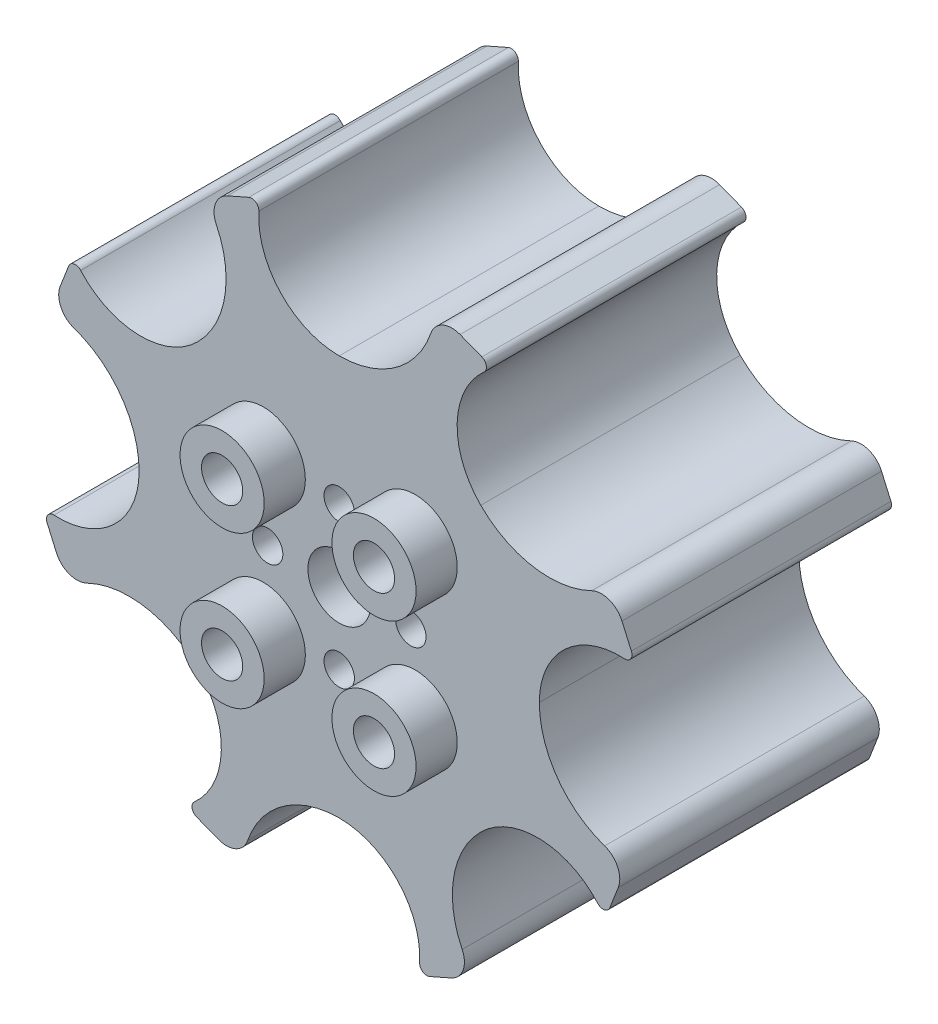
SolidWorks part; units mm, degrees
material "6061-T6 (SS)"
ref_plane "前视基准面" through (0, 0, 0) normal (0, 0, 1) x (1, 0, 0)
ref_plane "上视基准面" through (0, 0, 0) normal (0, 1, 0) x (1, 0, 0)
ref_plane "右视基准面" through (0, 0, 0) normal (1, 0, 0) x (0, 0, -1)
sketch "草图1" plane through (0, 0, 0) normal (0, 0, 1) x (1, 0, 0)
  line L0 (0, 31.3575) -> (0, 0) construction
  line L1 (0, 0) -> (22.1731, 22.1731) construction
  line L4 (0, 31.3575) -> (22.1731, 22.1731) construction
  line L6 (11.6409, 26.5357) -> (12.5976, 28.8454) construction
  line L7 (22.2808, 22.9688) -> (16.1797, 28.8872) construction
  line L8 (22.2808, 22.9688) -> (28.5472, 29.4288) construction
  line L9 (15.9368, 30.2296) -> (13.5034, 31.1755)
  line L17 (0, 33.18) -> (0, 31.3575) construction
  line L18 (32.6446, 10.1066) -> (31.5928, 12.4961)
  line L19 (30.2296, -15.9368) -> (31.1755, -13.5034)
  line L20 (10.1066, -32.6446) -> (12.4961, -31.5928)
  line L21 (-15.9368, -30.2296) -> (-13.5034, -31.1755)
  line L22 (-32.6446, -10.1066) -> (-31.5928, -12.4961)
  line L23 (-30.2296, 15.9368) -> (-31.1755, 13.5034)
  line L24 (-10.1066, 32.6446) -> (-12.4961, 31.5928)
  circle A0 centre (0, 0) radius 31.3575 construction
  arc A9 (16.1797, 28.8872) -> (15.8091, 15.8091) centre (22.1731, 22.1731) ccw
  circle A13 centre (0, 0) radius 41 construction
  arc A16 (16.1797, 28.8872) -> (15.9368, 30.2296) centre (15.6469, 29.484) ccw
  arc A17 (13.5034, 31.1755) -> (10.2336, 29.6588) centre (12.5976, 28.8454) ccw
  arc A18 (0, 22.3575) -> (10.2336, 29.6588) centre (0, 33.18) ccw
  arc A19 (15.8091, 15.8091) -> (28.2082, 13.7357) centre (23.4618, 23.4618) ccw
  arc A20 (31.5928, 12.4961) -> (28.2082, 13.7357) centre (29.3046, 11.4889) ccw
  arc A21 (31.8671, 8.9856) -> (32.6446, 10.1066) centre (31.9124, 9.7843) ccw
  arc A22 (31.8671, 8.9856) -> (22.3575, 0) centre (31.3575, 0) ccw
  arc A23 (22.3575, 0) -> (29.6588, -10.2336) centre (33.18, 0) ccw
  arc A24 (31.1755, -13.5034) -> (29.6588, -10.2336) centre (28.8454, -12.5976) ccw
  arc A25 (28.8872, -16.1797) -> (30.2296, -15.9368) centre (29.484, -15.6469) ccw
  arc A26 (28.8872, -16.1797) -> (15.8091, -15.8091) centre (22.1731, -22.1731) ccw
  arc A27 (15.8091, -15.8091) -> (13.7357, -28.2082) centre (23.4618, -23.4618) ccw
  arc A28 (12.4961, -31.5928) -> (13.7357, -28.2082) centre (11.4889, -29.3046) ccw
  arc A29 (8.9856, -31.8671) -> (10.1066, -32.6446) centre (9.7843, -31.9124) ccw
  arc A30 (8.9856, -31.8671) -> (0, -22.3575) centre (0, -31.3575) ccw
  arc A31 (0, -22.3575) -> (-10.2336, -29.6588) centre (0, -33.18) ccw
  arc A32 (-13.5034, -31.1755) -> (-10.2336, -29.6588) centre (-12.5976, -28.8454) ccw
  arc A33 (-16.1797, -28.8872) -> (-15.9368, -30.2296) centre (-15.6469, -29.484) ccw
  arc A34 (-16.1797, -28.8872) -> (-15.8091, -15.8091) centre (-22.1731, -22.1731) ccw
  arc A35 (-15.8091, -15.8091) -> (-28.2082, -13.7357) centre (-23.4618, -23.4618) ccw
  arc A36 (-31.5928, -12.4961) -> (-28.2082, -13.7357) centre (-29.3046, -11.4889) ccw
  arc A37 (-31.8671, -8.9856) -> (-32.6446, -10.1066) centre (-31.9124, -9.7843) ccw
  arc A38 (-31.8671, -8.9856) -> (-22.3575, 0) centre (-31.3575, 0) ccw
  arc A39 (-22.3575, 0) -> (-29.6588, 10.2336) centre (-33.18, 0) ccw
  arc A40 (-31.1755, 13.5034) -> (-29.6588, 10.2336) centre (-28.8454, 12.5976) ccw
  arc A41 (-28.8872, 16.1797) -> (-30.2296, 15.9368) centre (-29.484, 15.6469) ccw
  arc A42 (-28.8872, 16.1797) -> (-15.8091, 15.8091) centre (-22.1731, 22.1731) ccw
  arc A43 (-15.8091, 15.8091) -> (-13.7357, 28.2082) centre (-23.4618, 23.4618) ccw
  arc A44 (-12.4961, 31.5928) -> (-13.7357, 28.2082) centre (-11.4889, 29.3046) ccw
  arc A45 (-8.9856, 31.8671) -> (-10.1066, 32.6446) centre (-9.7843, 31.9124) ccw
  arc A46 (-8.9856, 31.8671) -> (0, 22.3575) centre (0, 31.3575) ccw
  point P91 (0, 0)
  point P98 (0, 0)
  dimension "D1" = 9
  dimension "D3" = 45
  dimension "D4" = 8
  dimension "D5" = 9
  dimension "D8" = 82
  dimension "D9" = 9
  dimension "D10" = 2.5
  dimension "D11" = 0.8
  dimension "D2" = 24
  dimension "D6" = 11.4
  dimension "D7" = 2.5
  dimension "D13" = 8.5
extrude "凸台-拉伸1" add sketch "草图1" along normal blind 25
sketch "草图2" plane through (0, 0, 0) normal (0, 0, -1) x (-1, 0, 0)
  line L0 (0, 0) -> (22.3575, 0) construction
  line L1 (0, 0) -> (15.8091, -15.8091) construction
  arc A0 (19.3575, 0) -> (21.9475, -7.4466) centre (31.3575, 0) ccw
  arc A1 (21.0346, -9.8541) -> (13.6878, -13.6878) centre (23.4618, -23.4618) ccw
  arc A2 (21.0346, -9.8541) -> (21.9475, -7.4466) centre (20.7712, -8.3774) ccw
  arc A3 (22.3575, 0) -> (31.8671, -8.9856) centre (31.3575, 0) ccw construction
  arc A4 (13.6878, -13.6878) -> (10.2537, -20.7847) centre (22.1731, -22.1731) ccw
  arc A5 (7.9058, -21.8416) -> (10.2537, -20.7847) centre (8.7638, -20.6112) ccw
  arc A27 (28.2082, -13.7357) -> (15.8091, -15.8091) centre (23.4618, -23.4618) ccw construction
  arc A28 (7.9058, -21.8416) -> (0, -19.3575) centre (0, -33.18) ccw
  arc A29 (0, -19.3575) -> (-7.4466, -21.9475) centre (0, -31.3575) ccw
  arc A30 (-9.8541, -21.0346) -> (-7.4466, -21.9475) centre (-8.3774, -20.7712) ccw
  arc A31 (-9.8541, -21.0346) -> (-13.6878, -13.6878) centre (-23.4618, -23.4618) ccw
  arc A32 (-13.6878, -13.6878) -> (-20.7847, -10.2537) centre (-22.1731, -22.1731) ccw
  arc A33 (-21.8416, -7.9058) -> (-20.7847, -10.2537) centre (-20.6112, -8.7638) ccw
  arc A34 (-21.8416, -7.9058) -> (-19.3575, 0) centre (-33.18, 0) ccw
  arc A35 (-19.3575, 0) -> (-21.9475, 7.4466) centre (-31.3575, 0) ccw
  arc A36 (-21.0346, 9.8541) -> (-21.9475, 7.4466) centre (-20.7712, 8.3774) ccw
  arc A37 (-21.0346, 9.8541) -> (-13.6878, 13.6878) centre (-23.4618, 23.4618) ccw
  arc A38 (-13.6878, 13.6878) -> (-10.2537, 20.7847) centre (-22.1731, 22.1731) ccw
  arc A39 (-7.9058, 21.8416) -> (-10.2537, 20.7847) centre (-8.7638, 20.6112) ccw
  arc A40 (-7.9058, 21.8416) -> (0, 19.3575) centre (0, 33.18) ccw
  arc A41 (0, 19.3575) -> (7.4466, 21.9475) centre (0, 31.3575) ccw
  arc A42 (9.8541, 21.0346) -> (7.4466, 21.9475) centre (8.3774, 20.7712) ccw
  arc A43 (9.8541, 21.0346) -> (13.6878, 13.6878) centre (23.4618, 23.4618) ccw
  arc A44 (13.6878, 13.6878) -> (20.7847, 10.2537) centre (22.1731, 22.1731) ccw
  arc A45 (21.8416, 7.9058) -> (20.7847, 10.2537) centre (20.6112, 8.7638) ccw
  arc A46 (21.8416, 7.9058) -> (19.3575, 0) centre (33.18, 0) ccw
  point P69 (0, 0)
  dimension "D1" = 3
  dimension "D2" = 3
  dimension "D3" = 1.5
  dimension "D4" = 8
extrude "切除-拉伸1" cut sketch "草图2" against normal through all
sketch "草图3" plane through (0, 0, 25) normal (0, 0, 1) x (1, 0, 0)
  line L8 (15.9368, 30.2296) -> (13.5034, 31.1755)
  line L9 (-10.1066, 32.6446) -> (-12.4961, 31.5928)
  line L10 (-30.2296, 15.9368) -> (-31.1755, 13.5034)
  line L11 (-32.6446, -10.1066) -> (-31.5928, -12.4961)
  line L12 (-15.9368, -30.2296) -> (-13.5034, -31.1755)
  line L13 (10.1066, -32.6446) -> (12.4961, -31.5928)
  line L14 (30.2296, -15.9368) -> (31.1755, -13.5034)
  line L15 (32.6446, 10.1066) -> (31.5928, 12.4961)
  line L16 (15.9368, 30.2296) -> (13.5034, 31.1755)
  line L17 (-10.1066, 32.6446) -> (-12.4961, 31.5928)
  line L18 (-30.2296, 15.9368) -> (-31.1755, 13.5034)
  line L19 (-32.6446, -10.1066) -> (-31.5928, -12.4961)
  line L20 (-15.9368, -30.2296) -> (-13.5034, -31.1755)
  line L21 (10.1066, -32.6446) -> (12.4961, -31.5928)
  line L22 (30.2296, -15.9368) -> (31.1755, -13.5034)
  line L23 (32.6446, 10.1066) -> (31.5928, 12.4961)
  arc A32 (15.8091, 15.8091) -> (28.2082, 13.7357) centre (23.4618, 23.4618) ccw
  arc A33 (16.1797, 28.8872) -> (15.8091, 15.8091) centre (22.1731, 22.1731) ccw
  arc A34 (16.1797, 28.8872) -> (15.9368, 30.2296) centre (15.6469, 29.484) ccw
  arc A35 (13.5034, 31.1755) -> (10.2336, 29.6588) centre (12.5976, 28.8454) ccw
  arc A36 (0, 22.3575) -> (10.2336, 29.6588) centre (0, 33.18) ccw
  arc A37 (-8.9856, 31.8671) -> (0, 22.3575) centre (0, 31.3575) ccw
  arc A38 (-8.9856, 31.8671) -> (-10.1066, 32.6446) centre (-9.7843, 31.9124) ccw
  arc A39 (-12.4961, 31.5928) -> (-13.7357, 28.2082) centre (-11.4889, 29.3046) ccw
  arc A40 (-15.8091, 15.8091) -> (-13.7357, 28.2082) centre (-23.4618, 23.4618) ccw
  arc A41 (-28.8872, 16.1797) -> (-15.8091, 15.8091) centre (-22.1731, 22.1731) ccw
  arc A42 (-28.8872, 16.1797) -> (-30.2296, 15.9368) centre (-29.484, 15.6469) ccw
  arc A43 (-31.1755, 13.5034) -> (-29.6588, 10.2336) centre (-28.8454, 12.5976) ccw
  arc A44 (-22.3575, 0) -> (-29.6588, 10.2336) centre (-33.18, 0) ccw
  arc A45 (-31.8671, -8.9856) -> (-22.3575, 0) centre (-31.3575, 0) ccw
  arc A46 (-31.8671, -8.9856) -> (-32.6446, -10.1066) centre (-31.9124, -9.7843) ccw
  arc A47 (-31.5928, -12.4961) -> (-28.2082, -13.7357) centre (-29.3046, -11.4889) ccw
  arc A48 (-15.8091, -15.8091) -> (-28.2082, -13.7357) centre (-23.4618, -23.4618) ccw
  arc A49 (-16.1797, -28.8872) -> (-15.8091, -15.8091) centre (-22.1731, -22.1731) ccw
  arc A50 (-16.1797, -28.8872) -> (-15.9368, -30.2296) centre (-15.6469, -29.484) ccw
  arc A51 (-13.5034, -31.1755) -> (-10.2336, -29.6588) centre (-12.5976, -28.8454) ccw
  arc A52 (0, -22.3575) -> (-10.2336, -29.6588) centre (0, -33.18) ccw
  arc A53 (8.9856, -31.8671) -> (0, -22.3575) centre (0, -31.3575) ccw
  arc A54 (8.9856, -31.8671) -> (10.1066, -32.6446) centre (9.7843, -31.9124) ccw
  arc A55 (12.4961, -31.5928) -> (13.7357, -28.2082) centre (11.4889, -29.3046) ccw
  arc A56 (15.8091, -15.8091) -> (13.7357, -28.2082) centre (23.4618, -23.4618) ccw
  arc A57 (28.8872, -16.1797) -> (15.8091, -15.8091) centre (22.1731, -22.1731) ccw
  arc A58 (28.8872, -16.1797) -> (30.2296, -15.9368) centre (29.484, -15.6469) ccw
  arc A59 (31.1755, -13.5034) -> (29.6588, -10.2336) centre (28.8454, -12.5976) ccw
  arc A60 (22.3575, 0) -> (29.6588, -10.2336) centre (33.18, 0) ccw
  arc A61 (31.8671, 8.9856) -> (22.3575, 0) centre (31.3575, 0) ccw
  arc A62 (31.8671, 8.9856) -> (32.6446, 10.1066) centre (31.9124, 9.7843) ccw
  arc A63 (31.5928, 12.4961) -> (28.2082, 13.7357) centre (29.3046, 11.4889) ccw
  arc A64 (15.8091, 15.8091) -> (28.2082, 13.7357) centre (23.4618, 23.4618) ccw
  arc A65 (16.1797, 28.8872) -> (15.8091, 15.8091) centre (22.1731, 22.1731) ccw
  arc A66 (16.1797, 28.8872) -> (15.9368, 30.2296) centre (15.6469, 29.484) ccw
  arc A67 (13.5034, 31.1755) -> (10.2336, 29.6588) centre (12.5976, 28.8454) ccw
  arc A68 (0, 22.3575) -> (10.2336, 29.6588) centre (0, 33.18) ccw
  arc A69 (-8.9856, 31.8671) -> (0, 22.3575) centre (0, 31.3575) ccw
  arc A70 (-8.9856, 31.8671) -> (-10.1066, 32.6446) centre (-9.7843, 31.9124) ccw
  arc A71 (-12.4961, 31.5928) -> (-13.7357, 28.2082) centre (-11.4889, 29.3046) ccw
  arc A72 (-15.8091, 15.8091) -> (-13.7357, 28.2082) centre (-23.4618, 23.4618) ccw
  arc A73 (-28.8872, 16.1797) -> (-15.8091, 15.8091) centre (-22.1731, 22.1731) ccw
  arc A74 (-28.8872, 16.1797) -> (-30.2296, 15.9368) centre (-29.484, 15.6469) ccw
  arc A75 (-31.1755, 13.5034) -> (-29.6588, 10.2336) centre (-28.8454, 12.5976) ccw
  arc A76 (-22.3575, 0) -> (-29.6588, 10.2336) centre (-33.18, 0) ccw
  arc A77 (-31.8671, -8.9856) -> (-22.3575, 0) centre (-31.3575, 0) ccw
  arc A78 (-31.8671, -8.9856) -> (-32.6446, -10.1066) centre (-31.9124, -9.7843) ccw
  arc A79 (-31.5928, -12.4961) -> (-28.2082, -13.7357) centre (-29.3046, -11.4889) ccw
  arc A80 (-15.8091, -15.8091) -> (-28.2082, -13.7357) centre (-23.4618, -23.4618) ccw
  arc A81 (-16.1797, -28.8872) -> (-15.8091, -15.8091) centre (-22.1731, -22.1731) ccw
  arc A82 (-16.1797, -28.8872) -> (-15.9368, -30.2296) centre (-15.6469, -29.484) ccw
  arc A83 (-13.5034, -31.1755) -> (-10.2336, -29.6588) centre (-12.5976, -28.8454) ccw
  arc A84 (0, -22.3575) -> (-10.2336, -29.6588) centre (0, -33.18) ccw
  arc A85 (8.9856, -31.8671) -> (0, -22.3575) centre (0, -31.3575) ccw
  arc A86 (8.9856, -31.8671) -> (10.1066, -32.6446) centre (9.7843, -31.9124) ccw
  arc A87 (12.4961, -31.5928) -> (13.7357, -28.2082) centre (11.4889, -29.3046) ccw
  arc A88 (15.8091, -15.8091) -> (13.7357, -28.2082) centre (23.4618, -23.4618) ccw
  arc A89 (28.8872, -16.1797) -> (15.8091, -15.8091) centre (22.1731, -22.1731) ccw
  arc A90 (28.8872, -16.1797) -> (30.2296, -15.9368) centre (29.484, -15.6469) ccw
  arc A91 (31.1755, -13.5034) -> (29.6588, -10.2336) centre (28.8454, -12.5976) ccw
  arc A92 (22.3575, 0) -> (29.6588, -10.2336) centre (33.18, 0) ccw
  arc A93 (31.8671, 8.9856) -> (22.3575, 0) centre (31.3575, 0) ccw
  arc A94 (31.8671, 8.9856) -> (32.6446, 10.1066) centre (31.9124, 9.7843) ccw
  arc A95 (31.5928, 12.4961) -> (28.2082, 13.7357) centre (29.3046, 11.4889) ccw
  dimension "D1" = 0
extrude "凸台-拉伸2" add sketch "草图3" along normal blind 4
sketch "草图4" plane through (0, 0, 29) normal (0, 0, 1) x (1, 0, 0)
  line L0 (0, 0) -> (8, 0) construction
  line L1 (0, 0) -> (8.4853, 8.4853) construction
  circle A0 centre (0, 0) radius 3.5
  circle A1 centre (8, 0) radius 1.7
  circle A2 centre (0, -8) radius 1.7
  circle A3 centre (-8, 0) radius 1.7
  circle A4 centre (0, 8) radius 1.7
  circle A5 centre (8.4853, 8.4853) radius 2.3
  circle A6 centre (8.4853, -8.4853) radius 2.3
  circle A7 centre (-8.4853, -8.4853) radius 2.3
  circle A8 centre (-8.4853, 8.4853) radius 2.3
  point P14 (0, 0)
  point P22 (0, 0)
  dimension "D1" = 7
  dimension "D2" = 3.4
  dimension "D6" = 4.6
  dimension "D3" = 8
  dimension "D5" = 12
  dimension "D7" = 45
  dimension "D4" = 4
  dimension "D8" = 4
extrude "切除-拉伸2" cut sketch "草图4" against normal through all
sketch "草图5" plane through (0, 0, 29) normal (0, 0, 1) x (1, 0, 0)
  circle A1 centre (-8.4853, 8.4853) radius 4.7
  circle A5 centre (-8.4853, 8.4853) radius 2.3 construction
  circle A6 centre (-8.4853, 8.4853) radius 2.3
  circle A7 centre (0, 0) radius 12 construction
  circle A8 centre (8.4853, 8.4853) radius 4.7
  circle A9 centre (8.4853, 8.4853) radius 2.3
  circle A10 centre (8.4853, -8.4853) radius 4.7
  circle A11 centre (8.4853, -8.4853) radius 2.3
  circle A12 centre (-8.4853, -8.4853) radius 4.7
  circle A13 centre (-8.4853, -8.4853) radius 2.3
  point P21 (0, 0)
  dimension "D1" = 9.4
  dimension "D2" = 4
extrude "凸台-拉伸3" add sketch "草图5" along normal blind 4.6
